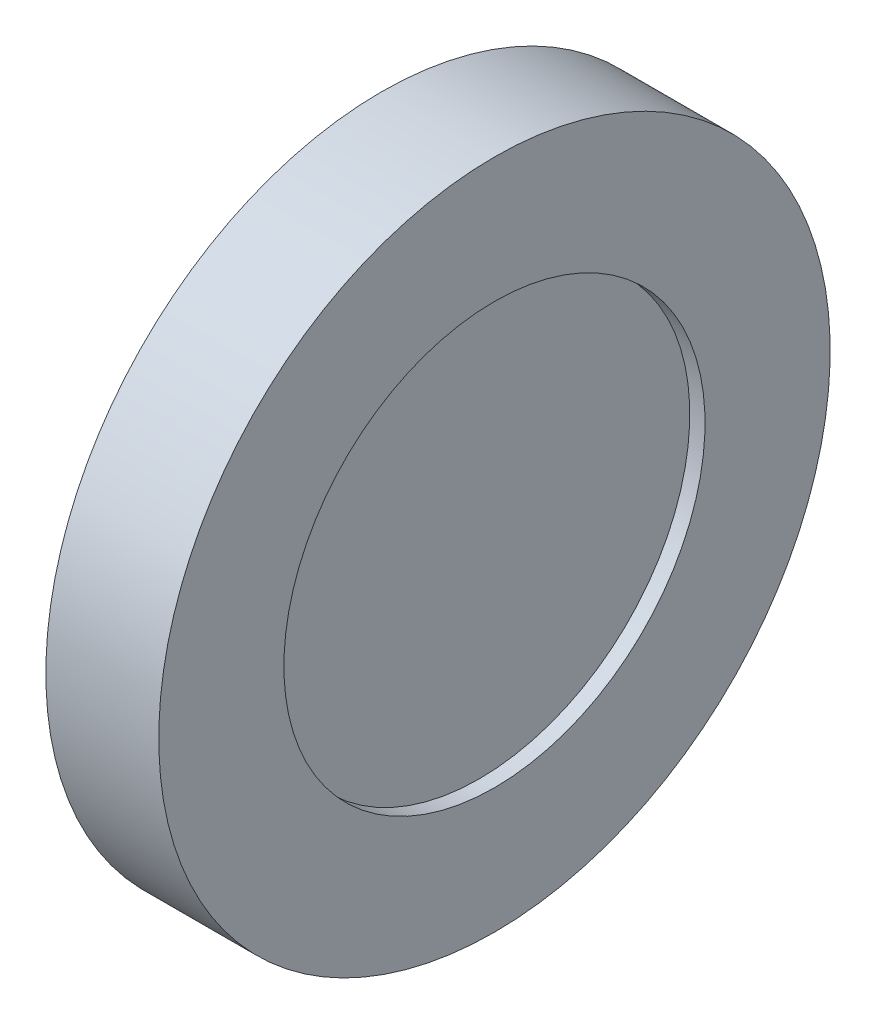
SolidWorks part; units mm, degrees
ref_plane "Front" through (0, 0, 0) normal (0, 0, 1) x (1, 0, 0)
ref_plane "Top" through (0, 0, 0) normal (0, 1, 0) x (1, 0, 0)
ref_plane "Right" through (0, 0, 0) normal (1, 0, 0) x (0, 0, -1)
sketch "Sketch1" plane through (0, 0, 0) normal (0, 0, 1) x (1, 0, 0)
  line L0 (-1.85, 6.9) -> (-1.35, 6.9)
  line L1 (-1.85, 0) -> (1.85, 0)
  line L2 (-1.85, 0) -> (-1.85, 11)
  line L3 (-1.85, 11) -> (1.85, 11)
  line L4 (1.85, 0) -> (1.85, 11)
  line L5 (-1.35, 6.9) -> (-1.35, 0)
  line L6 (1.85, 6.9) -> (1.35, 6.9)
  line L7 (1.35, 6.9) -> (1.35, 0)
  point P4 (0, 0)
  dimension "D1" = 3.7
  dimension "D2" = 11
  dimension "D3" = 6.9
  dimension "D4" = 0.5
revolve "Revolve1" add sketch "Sketch1" angle 360 about L1
